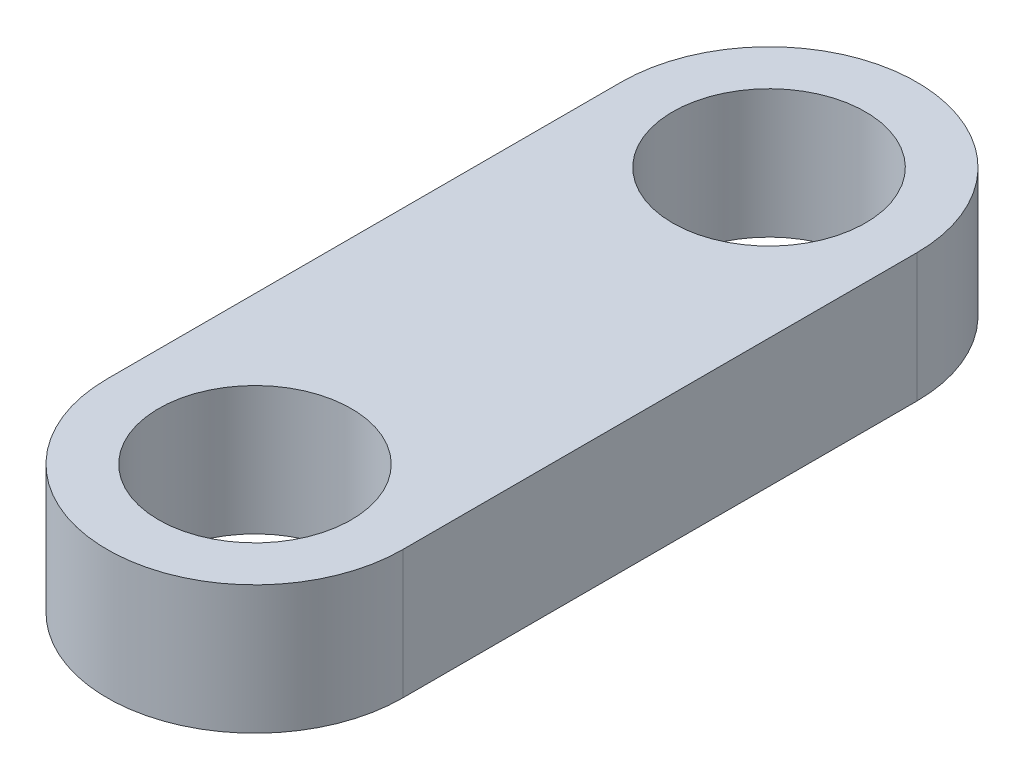
SolidWorks part; units mm, degrees
ref_plane "Front Plane" through (0, 0, 0) normal (0, 0, 1) x (1, 0, 0)
ref_plane "Top Plane" through (0, 0, 0) normal (0, 1, 0) x (1, 0, 0)
ref_plane "Right Plane" through (0, 0, 0) normal (1, 0, 0) x (0, 0, -1)
sketch "Sketch2" plane through (0, 0, 0) normal (0, 1, 0) x (1, 0, 0)
  line L0 (0, 0) -> (0, 20)
  line L1 (-5.75, 0) -> (-5.75, 20)
  line L2 (5.75, 20) -> (5.75, 0)
  line L3 (0, 25.75) -> (0, -5.75)
  circle A0 centre (0, 20) radius 3.75
  circle A1 centre (0, 0) radius 3.75
  circle A2 centre (0, 0) radius 5.75
  circle A3 centre (0, 20) radius 5.75
  dimension "D1" = 7.5
  dimension "D2" = 7.5
  dimension "D3" = 2
  dimension "D4" = 2
  dimension "D5" = 20
extrude "Boss-Extrude1" add sketch "Sketch2" along normal blind 5 contours L3 A2 A1 | L3 A2 A1 | A3 L0 A2 L2 | A3 L1 A2 L0 | L3 A3 A0 | L3 A3 A0 | L3 A1 L0 | L0 A1 L3
